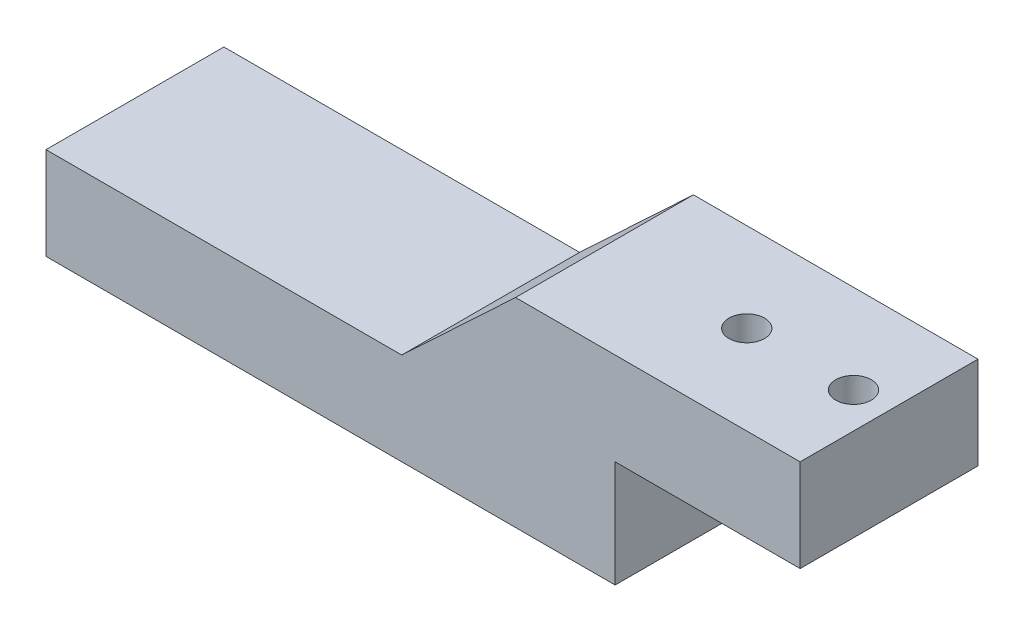
SolidWorks part; units mm, degrees
ref_plane "Front" through (0, 0, 0) normal (0, 0, 1) x (1, 0, 0)
ref_plane "Top" through (0, 0, 0) normal (0, 1, 0) x (1, 0, 0)
ref_plane "Right" through (0, 0, 0) normal (1, 0, 0) x (0, 0, -1)
sketch "Sketch1" plane through (0, 0, 0) normal (0, 0, 1) x (1, 0, 0)
  line L0 (0, 0) -> (55.2364, 0)
  line L1 (55.2364, 0) -> (55.2364, 15)
  line L2 (55.2364, 15) -> (81.2364, 15)
  line L3 (81.2364, 15) -> (81.2364, 28)
  line L4 (81.2364, 28) -> (41.2364, 28)
  line L5 (41.2364, 28) -> (25.2364, 13)
  line L6 (25.2364, 13) -> (-24.7636, 13)
  line L7 (-24.7636, 13) -> (-24.7636, 0)
  line L8 (-24.7636, 0) -> (0, 0)
  dimension "D1" = 13
  dimension "D2" = 15
  dimension "D3" = 13
  dimension "D4" = 26
  dimension "D5" = 80
  dimension "D6" = 50
  dimension "D7" = 40
extrude "Boss-Extrude1" add sketch "Sketch1" along normal blind 25
sketch "Sketch2" plane through (0, 28, 0) normal (0, 1, 0) x (1, 0, 0)
  line L0 (41.2364, -12.5) -> (81.2364, -12.5) construction
  line L1 (41.2364, -25) -> (41.2364, 0) construction
  line L2 (81.2364, -25) -> (81.2364, 0) construction
  circle A0 centre (76.2364, -12.5) radius 2.5
  circle A1 centre (61.2364, -12.5) radius 2.5
  dimension "D1" = 5
  dimension "D2" = 5
  dimension "D3" = 5
  dimension "D4" = 15
extrude "Cut-Extrude1" cut sketch "Sketch2" against normal through all
